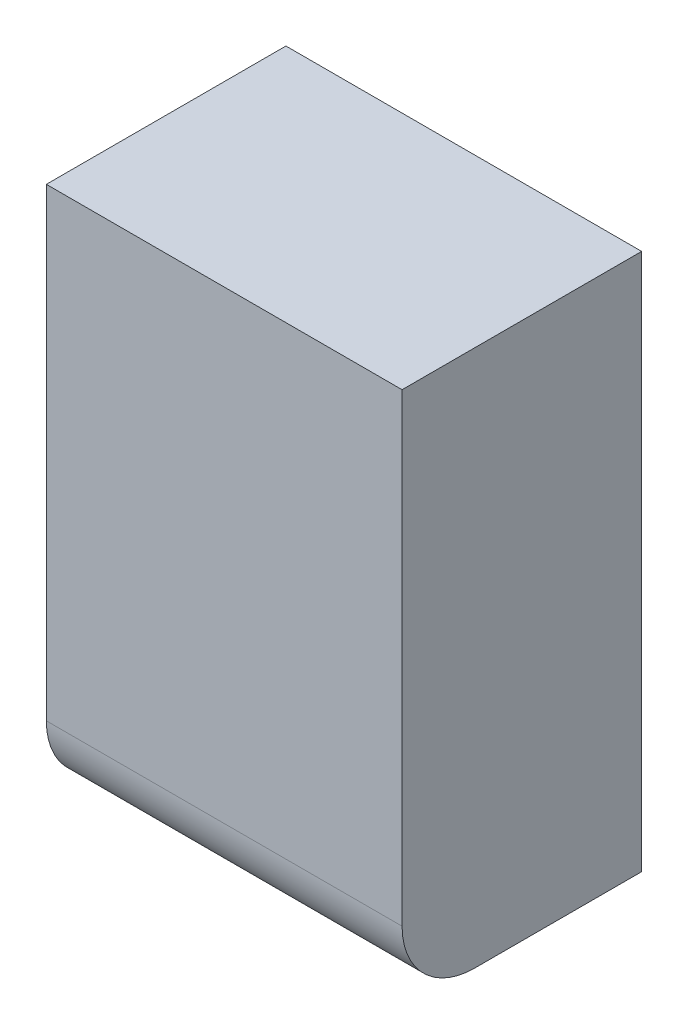
SolidWorks part; units mm, degrees
material "ABS"
ref_plane "Front Plane" through (0, 0, 0) normal (0, 0, 1) x (1, 0, 0)
ref_plane "Top Plane" through (0, 0, 0) normal (0, 1, 0) x (1, 0, 0)
ref_plane "Right Plane" through (0, 0, 0) normal (1, 0, 0) x (0, 0, -1)
sketch "Sketch1" plane through (0, 0, 0) normal (0, 0, 1) x (1, 0, 0)
  line L0 (0, 0) -> (-4.9, 0)
  line L1 (-4.9, 0) -> (-4.9, -7.4)
  line L2 (-4.9, -7.4) -> (0, -7.4)
  line L3 (0, -7.4) -> (0, 0)
  dimension "D1" = 7.4
  dimension "D2" = 4.9
extrude "Boss-Extrude1" add sketch "Sketch1" along normal blind 3.3
fillet "Fillet1" radius 1 1 edges at (-2.45, -7.4, 3.3)
